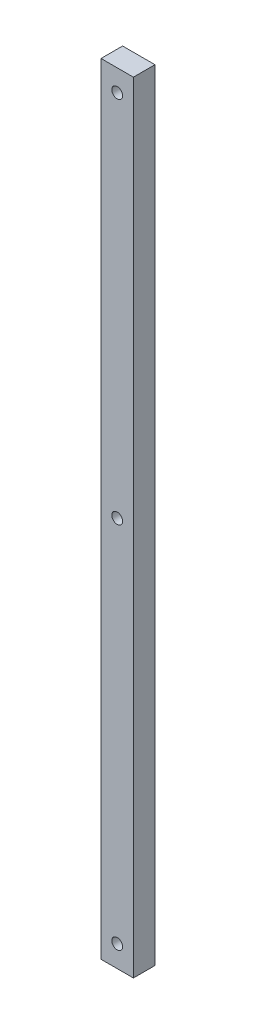
SolidWorks part; units mm, degrees
ref_plane "Front Plane" through (0, 0, 0) normal (0, 0, 1) x (1, 0, 0)
ref_plane "Top Plane" through (0, 0, 0) normal (0, 1, 0) x (1, 0, 0)
ref_plane "Right Plane" through (0, 0, 0) normal (1, 0, 0) x (0, 0, -1)
sketch "Sketch1" plane through (0, 0, 0) normal (0, 1, 0) x (1, 0, 0)
  line L1 (-159.7917, 19.5833) -> (-129.7917, 19.5833)
  line L2 (-159.7917, 19.5833) -> (-159.7917, -0.4167)
  line L3 (-159.7917, -0.4167) -> (-129.7917, -0.4167)
  line L4 (-129.7917, 19.5833) -> (-129.7917, -0.4167)
  dimension "D1" = 30
  dimension "D2" = 20
extrude "Boss-Extrude1" add sketch "Sketch1" along normal blind 723
sketch "Sketch2" plane through (0, 0, 0.4167) normal (0, 0, 1) x (1, 0, 0)
  line L0 (-159.7917, 723) -> (-159.7917, 703)
  line L1 (-159.7917, 723) -> (-159.7917, 0) construction
  line L2 (-159.7917, 703) -> (-129.7917, 703)
  line L3 (-129.7917, 723) -> (-129.7917, 0) construction
  line L4 (-159.7917, 0) -> (-159.7917, 20)
  line L5 (-159.7917, 20) -> (-129.7917, 20)
  line L6 (-159.7917, 723) -> (-159.7917, 0)
  line L7 (-159.7917, 361.5) -> (-129.7917, 361.5)
  circle A0 centre (-144.7917, 703) radius 5
  circle A1 centre (-144.7917, 20) radius 5
  circle A2 centre (-144.7917, 361.5) radius 5
  dimension "D1" = 20
  dimension "D2" = 20
extrude "Cut-Extrude1" cut sketch "Sketch2" against normal blind 25 contours L2 A0 | L2 A0 | L7 A2 | L7 A2 | L5 A1 | L5 A1
